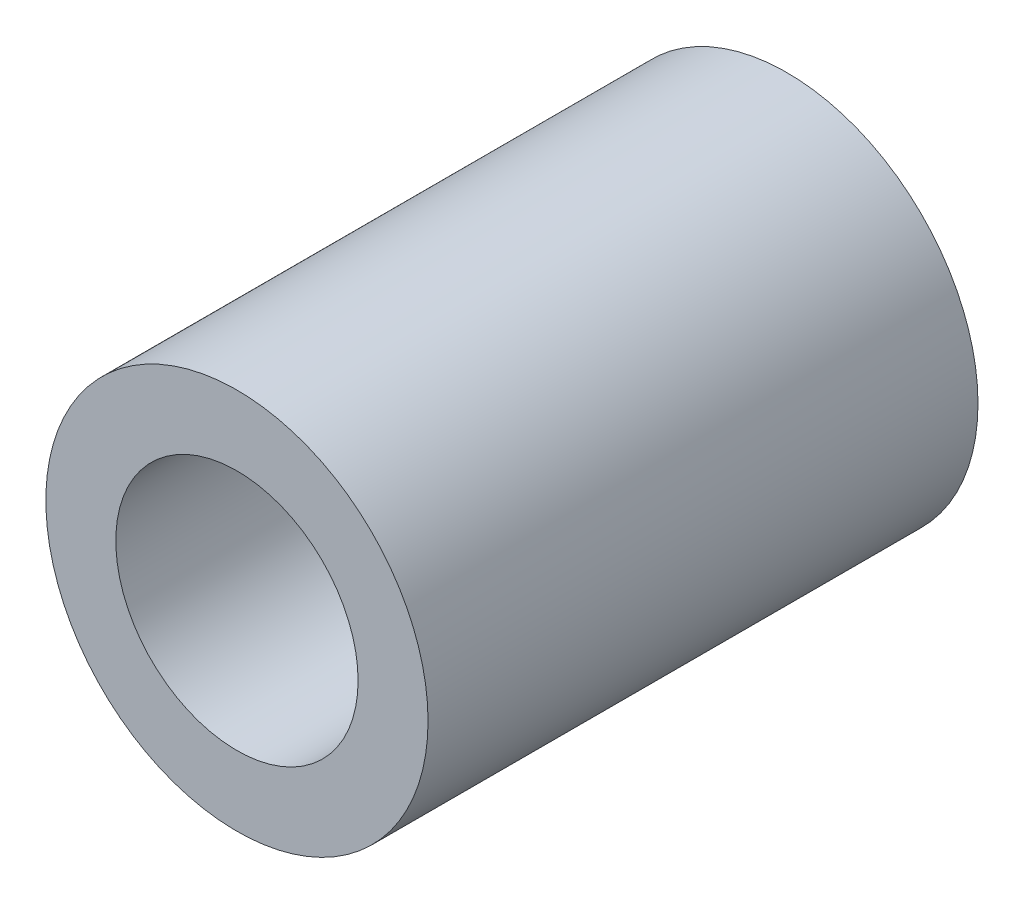
SolidWorks part; units mm, degrees
ref_plane "前视基准面" through (0, 0, 0) normal (0, 0, 1) x (1, 0, 0)
ref_plane "上视基准面" through (0, 0, 0) normal (0, 1, 0) x (1, 0, 0)
ref_plane "右视基准面" through (0, 0, 0) normal (1, 0, 0) x (0, 0, -1)
other "Configuration Table"
sketch "草图1" plane through (0, 0, 0) normal (0, 0, 1) x (1, 0, 0)
  circle A0 centre (0, 0) radius 3.9613
extrude "拉伸-薄壁1" add sketch "草图1" along normal blind 3.9 and the other way blind 7.5 thin thin type one direction reverse wall 1.45
